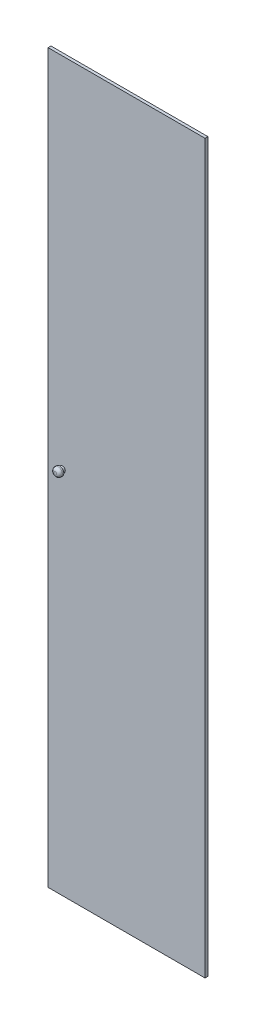
SolidWorks part; units mm, degrees
ref_plane "Front Plane" through (0, 0, 0) normal (0, 0, 1) x (1, 0, 0)
ref_plane "Top Plane" through (0, 0, 0) normal (0, 1, 0) x (1, 0, 0)
ref_plane "Right Plane" through (0, 0, 0) normal (1, 0, 0) x (0, 0, -1)
sketch "Sketch1" plane through (0, 0, 0) normal (0, 0, 1) x (1, 0, 0)
  line L1 (275, -1275) -> (-275, -1275)
  line L2 (275, -1275) -> (275, 1275)
  line L3 (275, 1275) -> (-275, 1275)
  line L4 (-275, -1275) -> (-275, 1275)
  line L5 (275, -1275) -> (-275, 1275) construction
  line L6 (275, 1275) -> (-275, -1275) construction
  point P0 (0, 0)
extrude "Boss-Extrude1" add sketch "Sketch1" along normal blind 10
sketch "Sketch2" plane through (0, 0, 10) normal (0, 0, 1) x (1, 0, 0)
  line L0 (-275, 80.2258) -> (-275, 20)
  line L3 (-275, 1275) -> (-275, -1275) construction
  circle A0 centre (-225, 20) radius 10
extrude "Boss-Extrude2" add sketch "Sketch2" along normal blind 10 contours A0
sketch "Sketch3" plane through (0, 0, 20) normal (0, 0, 1) x (1, 0, 0)
  circle A0 centre (-225, 20) radius 15
extrude "Boss-Extrude3" add sketch "Sketch3" along normal blind 15
fillet "Fillet1" radius 10 1 edges at (-210, 20, 35)
